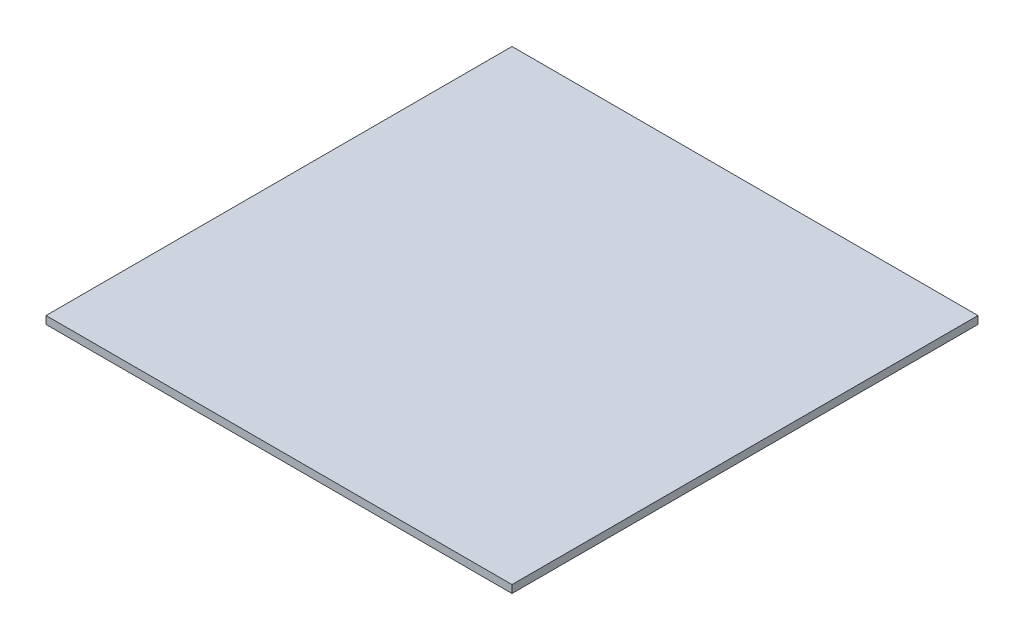
SolidWorks part; units mm, degrees
ref_plane "Front Plane" through (0, 0, 0) normal (0, 0, 1) x (1, 0, 0)
ref_plane "Top Plane" through (0, 0, 0) normal (0, 1, 0) x (1, 0, 0)
ref_plane "Right Plane" through (0, 0, 0) normal (1, 0, 0) x (0, 0, -1)
sketch "Sketch1" plane through (0, 0, 0) normal (0, 1, 0) x (1, 0, 0)
  line L0 (-14.7829, 60.8786) -> (-14.7829, -49.1214)
  line L1 (-164.7829, 100.8786) -> (135.2171, 100.8786)
  line L2 (-164.7829, 100.8786) -> (-164.7829, -199.1214)
  line L3 (-164.7829, -199.1214) -> (135.2171, -199.1214)
  line L4 (135.2171, 100.8786) -> (135.2171, -199.1214)
  line L5 (-14.7829, -49.1214) -> (80.4799, -104.1214)
  line L6 (-14.7829, -49.1214) -> (-110.0457, -104.1214)
  line L7 (-14.7829, -49.1214) -> (95.2171, -49.1214)
  circle A0 centre (-14.7829, -49.1214) radius 150
  circle A1 centre (-14.7829, -49.1214) radius 110
  circle A2 centre (-14.7829, 60.8786) radius 11.1185
  circle A3 centre (-110.0457, -104.1214) radius 11.3465
  circle A4 centre (80.4799, -104.1214) radius 8.8893
  circle A5 centre (95.2171, -49.1214) radius 11.5057
  point P7 (-14.7829, 60.8786)
  point P12 (-110.0457, -104.1214)
  point P13 (80.4799, -104.1214)
  dimension "D3" = 220
  dimension "D1" = 300
  dimension "D2" = 300
  dimension "D4" = 120
  dimension "D5" = 120
extrude "Boss-Extrude1" add sketch "Sketch1" along normal blind 5 contours L2 L3 L4 L1
